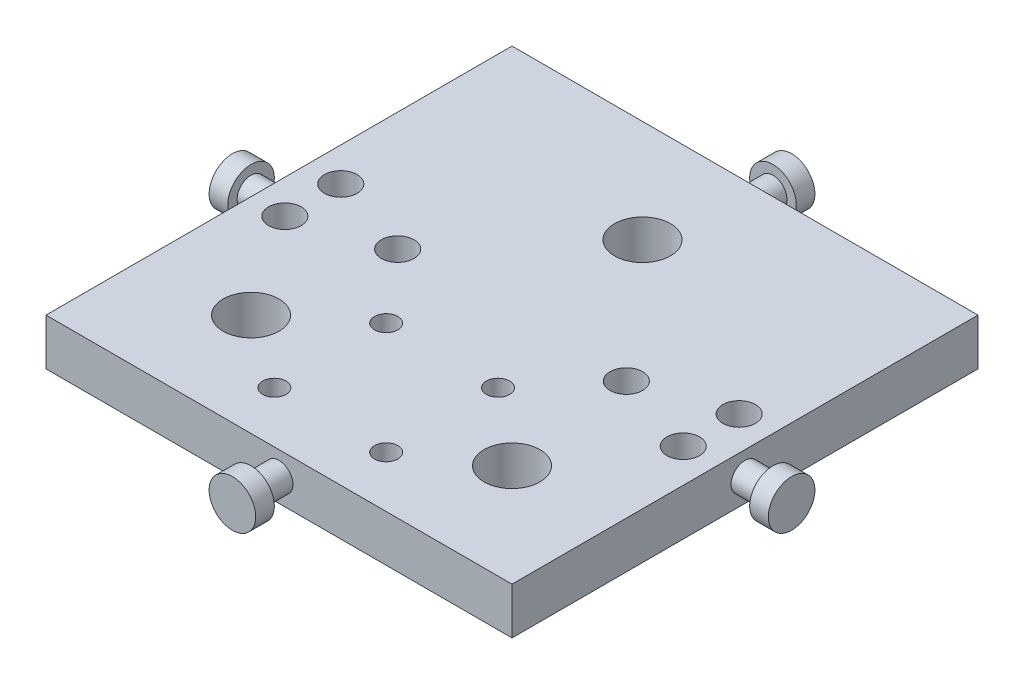
SolidWorks part; units mm, degrees
ref_plane "前视基准面" through (0, 0, 0) normal (0, 0, 1) x (1, 0, 0)
ref_plane "上视基准面" through (0, 0, 0) normal (0, 1, 0) x (1, 0, 0)
ref_plane "右视基准面" through (0, 0, 0) normal (1, 0, 0) x (0, 0, -1)
sketch "草图1" plane through (0, 0, 0) normal (0, 1, 0) x (1, 0, 0)
  line L1 (0, 0) -> (50, 0)
  line L2 (0, 0) -> (0, 50)
  line L3 (0, 50) -> (50, 50)
  line L4 (50, 0) -> (50, 50)
  dimension "D1" = 50
  dimension "D2" = 50
extrude "凸台-拉伸1" add sketch "草图1" along normal blind 5
sketch "草图2" plane through (0, 5, 0) normal (0, 1, 0) x (1, 0, 0)
  line L0 (0, 11) -> (11, 11) construction
  line L1 (0, 50) -> (0, 0) construction
  line L2 (11, 11) -> (11, 0) construction
  line L3 (0, 0) -> (50, 0) construction
  line L4 (50, 11) -> (39, 11) construction
  line L5 (50, 0) -> (50, 50) construction
  line L6 (39, 11) -> (39, 0) construction
  line L7 (25, 39) -> (25, 50) construction
  line L9 (50, 50) -> (0, 50) construction
  circle A0 centre (25, 39) radius 3
  circle A1 centre (11, 11) radius 3
  circle A2 centre (39, 11) radius 3
  dimension "D1" = 6
  dimension "D2" = 11
extrude "切除-拉伸1" cut sketch "草图2" against normal through all
sketch "草图3" plane through (0, 5, 0) normal (0, 1, 0) x (1, 0, 0)
  line L0 (25, 39) -> (25, 11.5) construction
  line L1 (25, 5.5) -> (25, 0) construction
  line L2 (19, 17.5) -> (31, 17.5) construction
  line L3 (19, 17.5) -> (19, 5.5) construction
  line L4 (19, 5.5) -> (31, 5.5) construction
  line L5 (31, 17.5) -> (31, 5.5) construction
  line L6 (0, 0) -> (50, 0) construction
  line L7 (25, 11.5) -> (31, 11.5) construction
  circle A0 centre (25, 11.5) radius 5 construction
  circle A1 centre (11, 11) radius 3 construction
  circle A4 centre (19, 17.5) radius 1.25
  circle A5 centre (31, 17.5) radius 1.25
  circle A6 centre (19, 5.5) radius 1.25
  circle A7 centre (31, 5.5) radius 1.25
  dimension "D2" = 10
  dimension "D5" = 2.5
  dimension "D1" = 0.5
  dimension "D3" = 12
  dimension "D4" = 12
extrude "切除-拉伸2" cut sketch "草图3" against normal through all
sketch "草图7" plane through (0, 0, 0) normal (0, -1, 0) x (1, 0, 0)
  line L0 (0, -50) -> (0, 0) construction
  line L1 (37.2645, -25) -> (50, -25) construction
  line L2 (50, 0) -> (50, -50) construction
  line B0 (50, -35) -> (50, -15)
  line B1 (42.2787, -21.5) -> (7.7213, -21.5)
  circle B2 centre (46.3725, -22) radius 1.25
  arc B3 (42.2787, -21.5) -> (49.247, -15) centre (39, -11) ccw
  circle B4 centre (46.3725, -28) radius 1.25
  circle B5 centre (12.7355, -25) radius 1.25
  circle B6 centre (3.6275, -28) radius 1.25
  line B7 (0, -15) -> (0, -35)
  circle B8 centre (3.6275, -22) radius 1.25
  circle B9 centre (37.2645, -25) radius 1.25
  line B10 (7.7213, -28.5) -> (42.2787, -28.5)
  arc B11 (49.247, -35) -> (42.2787, -28.5) centre (39, -39) ccw
sketch_block_instance "块1-2"
sketch_block "块1"
sketch "草图8" plane through (0, 0, 0) normal (0, -1, 0) x (1, 0, 0)
  circle A0 centre (46.3725, -22) radius 1.75
  circle A1 centre (46.3725, -28) radius 1.75
  circle A2 centre (37.2645, -25) radius 1.75
  circle A3 centre (12.7355, -25) radius 1.75
  circle A4 centre (3.6275, -28) radius 1.75
  circle A5 centre (3.6275, -22) radius 1.75
  dimension "D1" = 3.5
extrude "切除-拉伸4" cut sketch "草图8" against normal through all
sketch "草图9" plane through (0, 0, 0) normal (0, 0, 1) x (1, 0, 0)
  line L0 (25, 2.5) -> (25, 0) construction
  line L1 (0, 0) -> (50, 0) construction
  line L2 (0, 5) -> (50, 5) construction
  circle A0 centre (25, 2.5) radius 2.5
extrude "凸台-拉伸2" add sketch "草图9" along normal blind 5
sketch "草图10" plane through (0, 0, 0) normal (0, 0, 1) x (1, 0, 0)
  circle A0 centre (25, 2.5) radius 1.5
  circle A1 centre (25, 2.5) radius 2.5
  dimension "D1" = 3
extrude "切除-拉伸5" cut sketch "草图10" along normal blind 3
sketch "草图11" plane through (50, 0, 0) normal (1, 0, 0) x (0, 0, -1)
  line L0 (0, 0) -> (50, 0) construction
  line L1 (0, 5) -> (50, 5) construction
  circle A0 centre (25, 2.5) radius 2.5
extrude "凸台-拉伸3" add sketch "草图11" along normal blind 5
sketch "草图12" plane through (50, 0, 0) normal (1, 0, 0) x (0, 0, -1)
  circle A0 centre (25, 2.5) radius 2.5
  circle A1 centre (25, 2.5) radius 1.5
  dimension "D1" = 3
extrude "切除-拉伸7" cut sketch "草图12" along normal blind 3
ref_plane "基准面1" through (25, 0, 0) normal (-1, 0, 0) x (0, 0, 1)
mirror "镜向1" about plane through (25, 0, 0) normal (-1, 0, 0) of "切除-拉伸7", "凸台-拉伸3"
ref_plane "基准面2" through (0, 0, -25) normal (0, 0, -1) x (-1, 0, 0)
mirror "镜向2" about plane through (0, 0, -25) normal (0, 0, -1) of "切除-拉伸5", "凸台-拉伸2"
